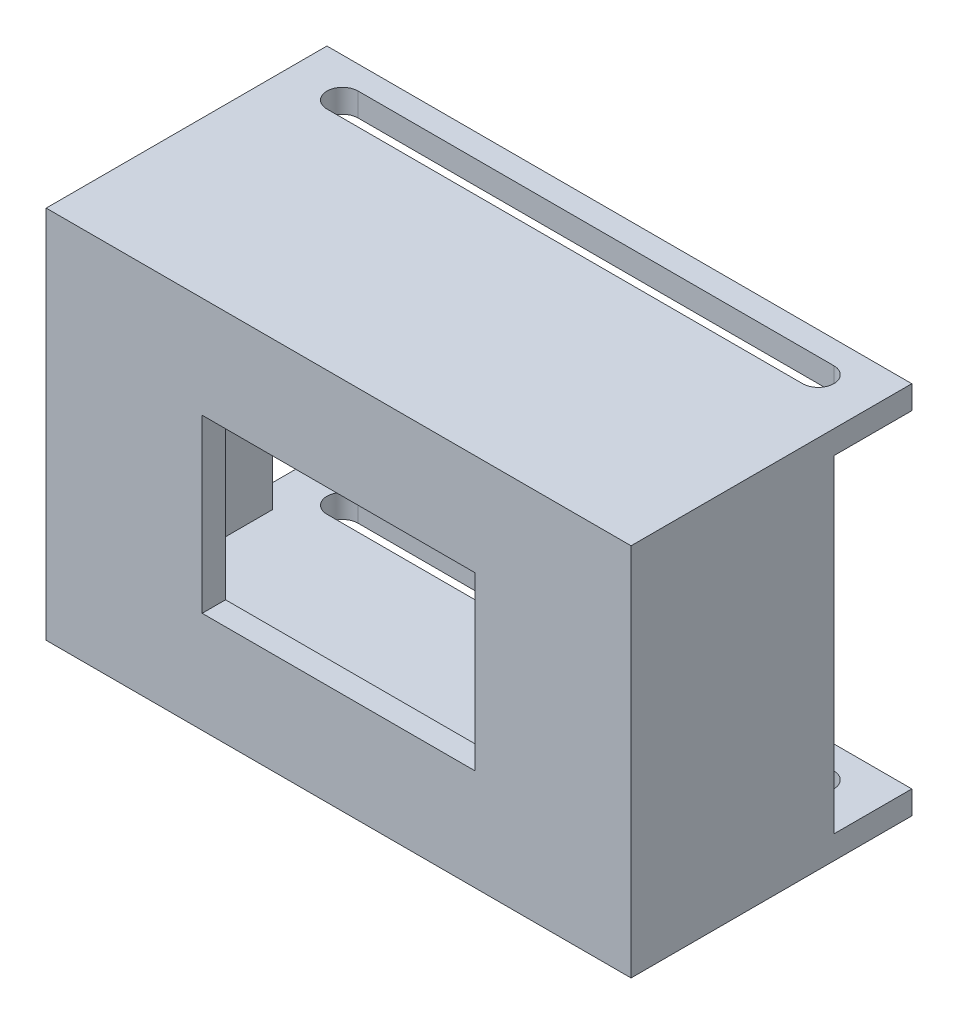
SolidWorks part; units mm, degrees
ref_plane "Front Plane" through (0, 0, 0) normal (0, 0, 1) x (1, 0, 0)
ref_plane "Top Plane" through (0, 0, 0) normal (0, 1, 0) x (1, 0, 0)
ref_plane "Right Plane" through (0, 0, 0) normal (1, 0, 0) x (0, 0, -1)
sketch "Sketch1" plane through (0, 0, 0) normal (0, 0, 1) x (1, 0, 0)
  line L1 (-37.5, 24) -> (37.5, 24)
  line L2 (-37.5, 24) -> (-37.5, -24)
  line L3 (-37.5, -24) -> (37.5, -24)
  line L4 (37.5, 24) -> (37.5, -24)
  line L5 (-37.5, 24) -> (37.5, -24) construction
  line L6 (-37.5, -24) -> (37.5, 24) construction
  point P0 (0, 0)
  dimension "D1" = 48
  dimension "D2" = 75
extrude "Boss-Extrude1" add sketch "Sketch1" along normal blind 3
sketch "Sketch2" plane through (0, 0, 3) normal (0, 0, 1) x (1, 0, 0)
  line L1 (-17.5, 11) -> (17.5, 11)
  line L2 (-17.5, 11) -> (-17.5, -11)
  line L3 (-17.5, -11) -> (17.5, -11)
  line L4 (17.5, 11) -> (17.5, -11)
  line L5 (-17.5, 11) -> (17.5, -11) construction
  line L6 (-17.5, -11) -> (17.5, 11) construction
  point P0 (0, 0)
  dimension "D1" = 22
  dimension "D2" = 35
extrude "Cut-Extrude1" cut sketch "Sketch2" against normal blind 3
sketch "Sketch3" plane through (0, 0, 0) normal (0, 0, -1) x (-1, 0, 0)
  line L0 (37.5, 24) -> (37.5, -24) construction
  line L1 (-37.5, 24) -> (37.5, 24)
  line L2 (-37.5, 24) -> (-37.5, 21)
  line L3 (-37.5, 21) -> (37.5, 21)
  line L4 (37.5, 24) -> (37.5, 21)
  line L5 (-37.5, -24) -> (-37.5, 24) construction
  line L6 (37.5, -24) -> (-37.5, -24)
  line L7 (37.5, -24) -> (37.5, -21)
  line L8 (37.5, -21) -> (-37.5, -21)
  line L9 (-37.5, -24) -> (-37.5, -21)
  dimension "D1" = 3
  dimension "D2" = 3
extrude "Boss-Extrude2" add sketch "Sketch3" along normal blind 33
sketch "Sketch4" plane through (0, 0, 0) normal (0, 0, -1) x (-1, 0, 0)
  line L0 (37.5, -21) -> (-37.5, -21) construction
  line L1 (-37.5, 21) -> (-34.5, 21)
  line L2 (-37.5, 21) -> (-37.5, -21)
  line L3 (-37.5, -21) -> (-34.5, -21)
  line L4 (-34.5, 21) -> (-34.5, -21)
  line L6 (37.5, 21) -> (34.5, 21)
  line L7 (37.5, 21) -> (37.5, -21)
  line L8 (37.5, -21) -> (34.5, -21)
  line L9 (34.5, 21) -> (34.5, -21)
  dimension "D1" = 3
  dimension "D2" = 3
extrude "Boss-Extrude3" add sketch "Sketch4" along normal blind 23
sketch "Sketch5" plane through (0, -24, 0) normal (0, -1, 0) x (1, 0, 0)
  line L0 (-30.5, -28) -> (30.5, -28) construction
  line L1 (-30.5, -26) -> (30.5, -26)
  line L2 (-30.5, -30) -> (30.5, -30)
  line L3 (37.5, -33) -> (-37.5, -33) construction
  line L4 (-37.5, 3) -> (-37.5, -33) construction
  line L5 (37.5, 3) -> (37.5, -33) construction
  arc A0 (-30.5, -26) -> (-30.5, -30) centre (-30.5, -28) ccw
  arc A1 (30.5, -30) -> (30.5, -26) centre (30.5, -28) ccw
  point P2 (0, -28)
  dimension "D1" = 2
  dimension "D3" = 7
  dimension "D4" = 7
  dimension "D2" = 5
extrude "Cut-Extrude2" cut sketch "Sketch5" against normal through all
